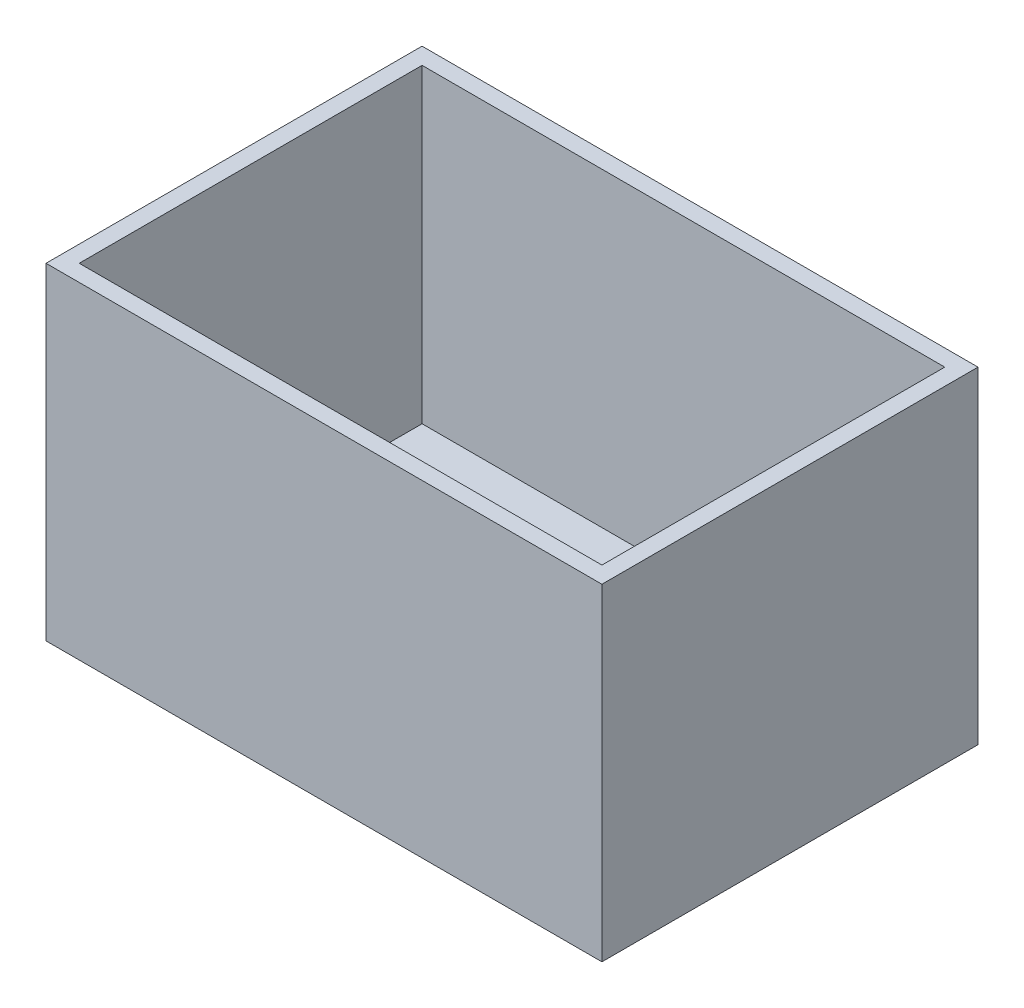
SolidWorks part; units mm, degrees
ref_plane "Front Plane" through (0, 0, 0) normal (0, 0, 1) x (1, 0, 0)
ref_plane "Top Plane" through (0, 0, 0) normal (0, 1, 0) x (1, 0, 0)
ref_plane "Right Plane" through (0, 0, 0) normal (1, 0, 0) x (0, 0, -1)
sketch "Sketch1" plane through (0, 0, 0) normal (0, 1, 0) x (1, 0, 0)
  line L1 (-85, -57.5) -> (85, -57.5)
  line L2 (-85, -57.5) -> (-85, 57.5)
  line L3 (-85, 57.5) -> (85, 57.5)
  line L4 (85, -57.5) -> (85, 57.5)
  line L5 (-85, -57.5) -> (85, 57.5) construction
  line L6 (-85, 57.5) -> (85, -57.5) construction
  point P0 (0, 0)
  dimension "D1" = 115
  dimension "D2" = 170
extrude "Boss-Extrude1" add sketch "Sketch1" along normal blind 100
shell "Shell1" thickness 5.08
